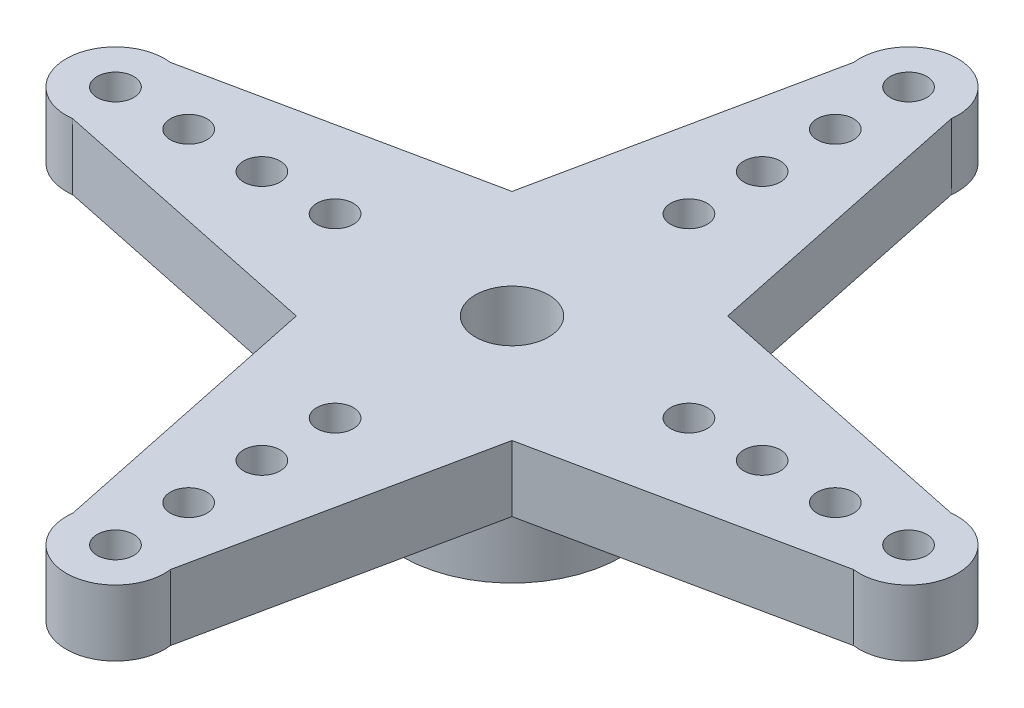
SolidWorks part; units mm, degrees
ref_plane "Front Plane" through (0, 0, 0) normal (0, 0, 1) x (1, 0, 0)
ref_plane "Top Plane" through (0, 0, 0) normal (0, 1, 0) x (1, 0, 0)
ref_plane "Right Plane" through (0, 0, 0) normal (1, 0, 0) x (0, 0, -1)
sketch "Sketch1" plane through (0, 0, 0) normal (0, 1, 0) x (1, 0, 0)
  circle A0 centre (0, 0) radius 4.5
  circle A1 centre (0, 0) radius 2.5
  dimension "D1" = 9
  dimension "D2" = 5
extrude "Boss-Extrude1" add sketch "Sketch1" along normal blind 3.6
sketch "Sketch2" plane through (0, 3.6, 0) normal (0, 1, 0) x (1, 0, 0)
  line L0 (0, 0) -> (-4.4194, 4.4194) construction
  line L1 (4.4194, 4.4194) -> (0, 0) construction
  line L2 (0, 0) -> (0, 4.5) construction
  line L3 (-2, 16) -> (-4.4194, 4.4194)
  line L4 (2, 16) -> (4.4194, 4.4194)
  line L5 (16, -2) -> (4.4194, -4.4194)
  line L6 (16, 2) -> (4.4194, 4.4194)
  line L7 (-2, -16) -> (-4.4194, -4.4194)
  line L8 (2, -16) -> (4.4194, -4.4194)
  line L9 (-16, 2) -> (-4.4194, 4.4194)
  line L10 (-16, -2) -> (-4.4194, -4.4194)
  circle A0 centre (0, 0) radius 1.5
  circle A1 centre (0, 7.25) radius 0.75
  circle A2 centre (0, 10.25) radius 0.75
  circle A3 centre (0, 13.25) radius 0.75
  circle A4 centre (0, 16.25) radius 0.75
  arc A5 (-2, 16) -> (2, 16) centre (0, 16.25) cw
  circle A6 centre (0, 0) radius 6.25
  circle A7 centre (0, 0) radius 4.5 construction
  arc A8 (16, 2) -> (16, -2) centre (16.25, 0) cw
  circle A9 centre (16.25, 0) radius 0.75
  circle A10 centre (13.25, 0) radius 0.75
  circle A11 centre (10.25, 0) radius 0.75
  circle A12 centre (7.25, 0) radius 0.75
  arc A13 (2, -16) -> (-2, -16) centre (0, -16.25) cw
  circle A14 centre (0, -16.25) radius 0.75
  circle A15 centre (0, -13.25) radius 0.75
  circle A16 centre (0, -10.25) radius 0.75
  circle A17 centre (0, -7.25) radius 0.75
  arc A18 (-16, -2) -> (-16, 2) centre (-16.25, 0) cw
  circle A19 centre (-16.25, 0) radius 0.75
  circle A20 centre (-13.25, 0) radius 0.75
  circle A21 centre (-10.25, 0) radius 0.75
  circle A22 centre (-7.25, 0) radius 0.75
  point P63 (0, 0)
  circle M1 centre (0, 0) radius 4.5
  circle M2 centre (0, 0) radius 2.5
  dimension "D1" = 3
  dimension "D2" = 7.25
  dimension "D3" = 1.5
  dimension "D5" = 4
  dimension "D7" = 12.5
  dimension "D8" = 90
  dimension "D9" = 45
  dimension "D4" = 4
extrude "Boss-Extrude2" add sketch "Sketch2" along normal blind 2.7 contours A13 L8 A6 L7 A17 A16 A15 A14 | A18 L10 A6 L9 A22 A21 A20 A19 | A6 M1 | A6 L4 A5 L3 A4 A3 A2 A1 | A8 L6 A6 L5 A12 A11 A10 A9 | M1 M2 | A0 M2
sketch "Sketch3" plane through (0, 3.6, 0) normal (0, -1, 0) x (1, 0, 0)
  line L1 (-4.8366, -2.3449) -> (-7.8366, -2.3449)
  line L2 (-4.8366, -2.3449) -> (-4.8366, -1.8449)
  line L3 (-4.8366, -1.8449) -> (-7.8366, -1.8449)
  line L4 (-7.8366, -2.3449) -> (-7.8366, -1.8449)
  line L5 (-2.706, -5.8283) -> (-2.206, -5.8283)
  line L6 (-2.706, -5.8283) -> (-2.706, -8.8283)
  line L7 (-2.706, -8.8283) -> (-2.206, -8.8283)
  line L8 (-2.206, -5.8283) -> (-2.206, -8.8283)
  dimension "D1" = 3
  dimension "D2" = 0.5
  dimension "D3" = 0.5
  dimension "D4" = 3
extrude "Boss-Extrude3" add sketch "Sketch3" along normal blind 0.5
